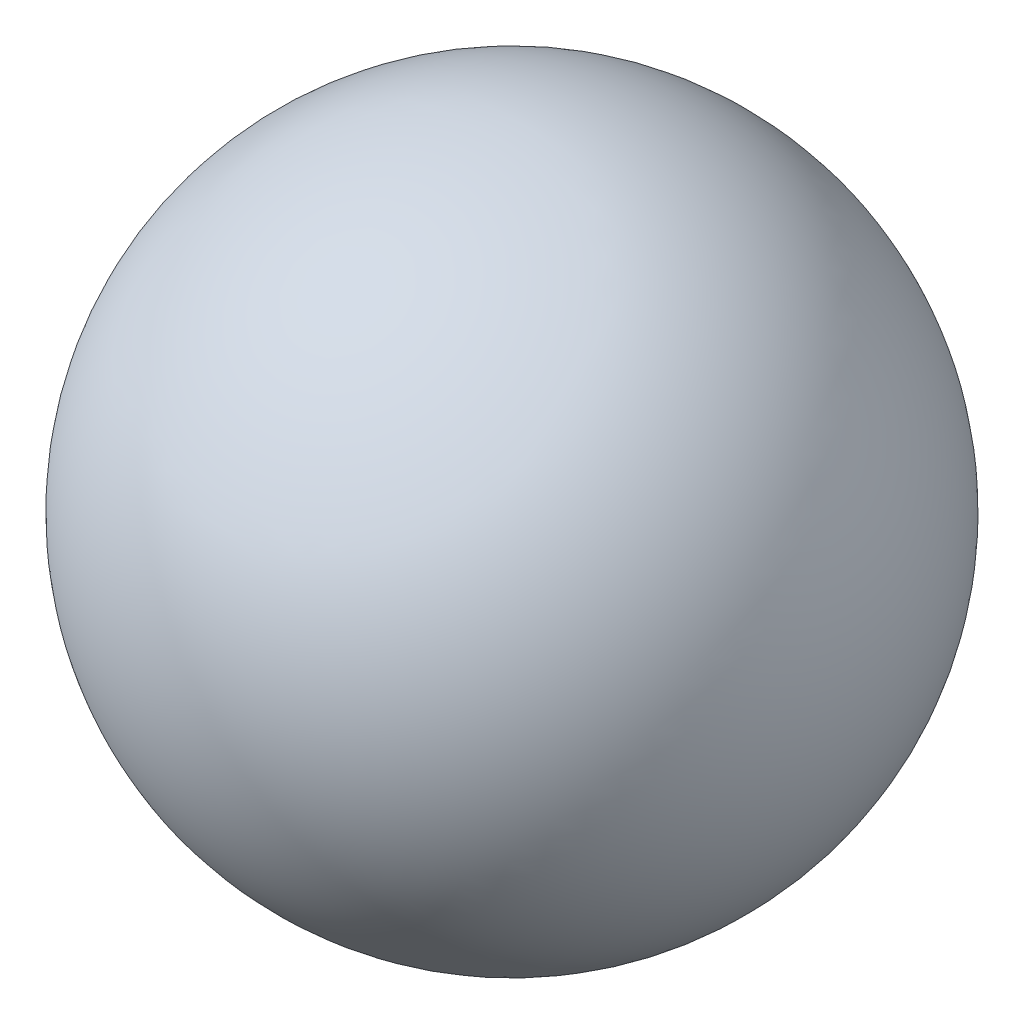
SolidWorks part; units mm, degrees
ref_plane "Front Plane" through (0, 0, 0) normal (0, 0, 1) x (1, 0, 0)
ref_plane "Top Plane" through (0, 0, 0) normal (0, 1, 0) x (1, 0, 0)
ref_plane "Right Plane" through (0, 0, 0) normal (1, 0, 0) x (0, 0, -1)
sketch "Sketch1" plane through (0, 0, 0) normal (1, 0, 0) x (0, 0, -1)
  line L0 (-3.5, 0) -> (3.5, 0) construction
  line L1 (0, 16) -> (0, -16) construction
  line L2 (3.15, 16) -> (-3.15, 16)
  line L3 (-3.15, 16) -> (-3.5, 15.65)
  line L4 (-3.5, 15.65) -> (-3.5, 14.0989)
  line L5 (-3.5, 14.0989) -> (-1.5556, 14.0989)
  line L6 (3.5, 14.0989) -> (1.5556, 14.0989)
  line L7 (3.5, 15.65) -> (3.5, 14.0989)
  line L8 (3.15, 16) -> (3.5, 15.65)
  line L9 (0, 16) -> (0, 13) construction
  line L10 (0, 13) -> (0, 10) construction
  arc A0 (-1.5556, 14.0989) -> (1.5556, 14.0989) centre (0, 13) cw
  point P14 (0, 10)
  dimension "D3" = 3.1111
  dimension "D1" = 45
  dimension "Width" = 7
  dimension "OD" = 32
  dimension "D2" = 0.35
  dimension "Shaft Dia" = 20
  dimension "D4" = 1.0989
sketch "Sketch4" plane through (0, 0, 0) normal (1, 0, 0) x (0, 0, -1)
  line L0 (-1.9046, 13) -> (1.9046, 13)
  arc A2 (-1.9046, 13) -> (1.9046, 13) centre (0, 13) cw
  arc A3 (1.5556, 14.0989) -> (-1.5556, 14.0989) centre (0, 13) ccw construction
revolve "Revolve4" add sketch "Sketch4" angle 360 about L0
delete or keep bodies "Body-Delete/Keep 1" type keep bodies bodies 104
